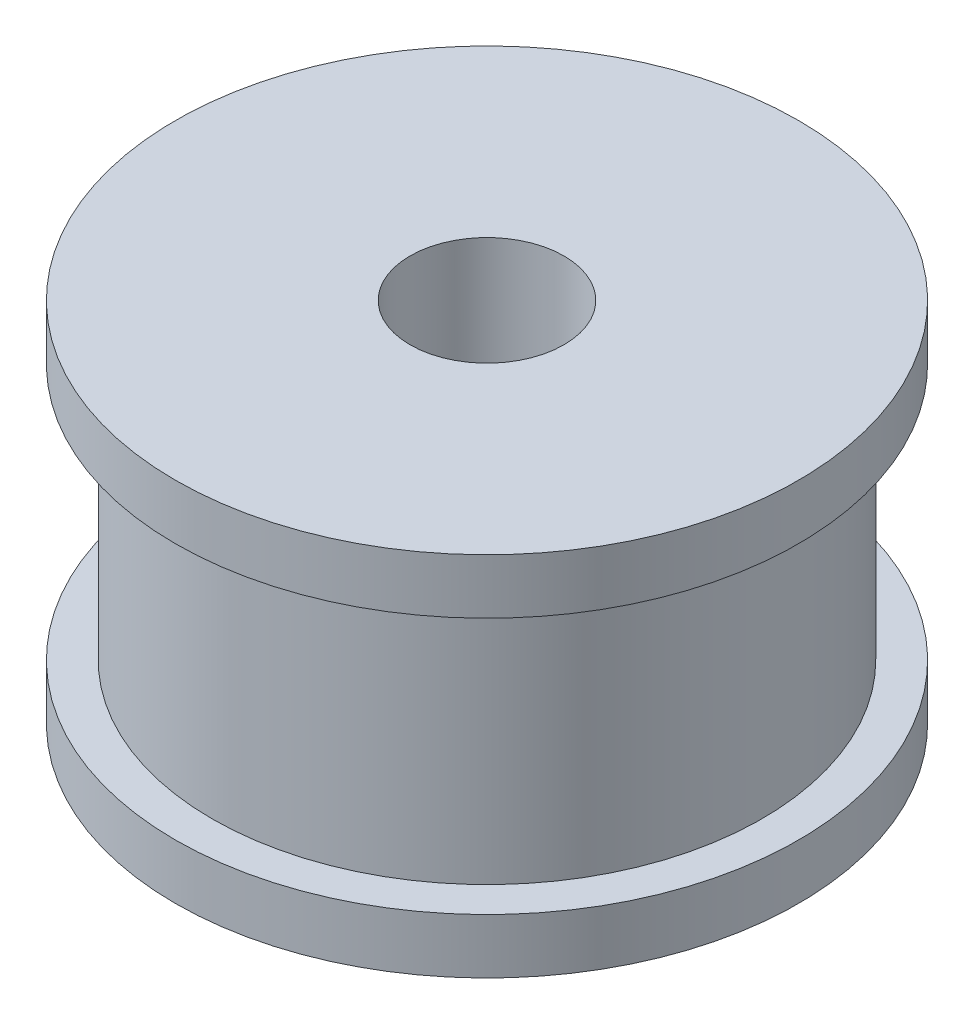
SolidWorks part; units mm, degrees
ref_plane "前视基准面" through (0, 0, 0) normal (0, 0, 1) x (1, 0, 0)
ref_plane "上视基准面" through (0, 0, 0) normal (0, 1, 0) x (1, 0, 0)
ref_plane "右视基准面" through (0, 0, 0) normal (1, 0, 0) x (0, 0, -1)
sketch "草图1" plane through (0, 0, 0) normal (0, 1, 0) x (1, 0, 0)
  circle A0 centre (0, 0) radius 7.5
  circle A1 centre (0, 0) radius 2.1
  dimension "D1" = 4.2
  dimension "D2" = 15
extrude "凸台-拉伸1" add sketch "草图1" along normal blind 7
sketch "草图2" plane through (0, 7, 0) normal (0, 1, 0) x (1, 0, 0)
  circle A0 centre (0, 0) radius 8.5
  circle A1 centre (0, 0) radius 7.5
  circle A2 centre (0, 0) radius 7.5 construction
  circle A3 centre (0, 0) radius 2.1 construction
  circle A4 centre (0, 0) radius 2.1
  dimension "D2" = 17
  dimension "D1" = 0
extrude "凸台-拉伸2" add sketch "草图2" along normal blind 1.5
sketch "草图3" plane through (0, 0, 0) normal (0, -1, 0) x (1, 0, 0)
  circle A0 centre (0, 0) radius 2.1 construction
  circle A1 centre (0, 0) radius 2.1
  circle A2 centre (0, 0) radius 8.5
extrude "凸台-拉伸3" add sketch "草图3" along normal blind 1.5
